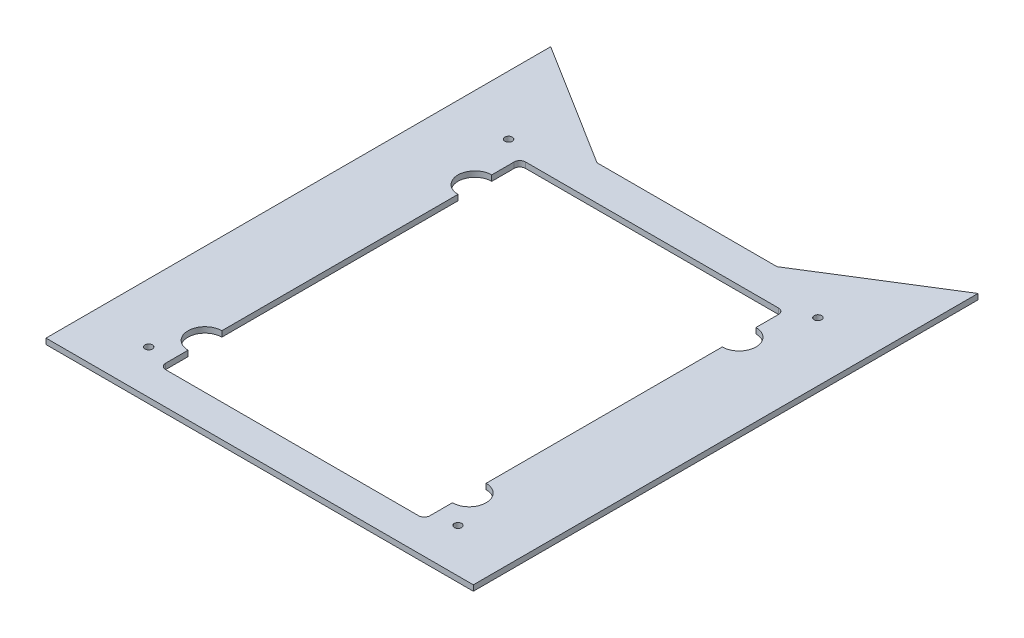
SolidWorks part; units mm, degrees
ref_plane "Front Plane" through (0, 0, 0) normal (0, 0, 1) x (1, 0, 0)
ref_plane "Top Plane" through (0, 0, 0) normal (0, 1, 0) x (1, 0, 0)
ref_plane "Right Plane" through (0, 0, 0) normal (1, 0, 0) x (0, 0, -1)
sketch "Sketch1" plane through (0, 0, 0) normal (0, 1, 0) x (1, 0, 0)
  line L17 (265.3132, -148.5502) -> (201.8132, -148.5502) construction
  line L18 (265.3132, -148.5502) -> (265.3132, -339.0502) construction
  line L19 (265.3132, -339.0502) -> (201.8132, -339.0502) construction
  line L20 (201.8132, -148.5502) -> (201.8132, -339.0502) construction
  line L21 (-153.7868, -148.5502) -> (-153.7868, -339.0502) construction
  line L22 (-217.2868, -339.0502) -> (-153.7868, -339.0502) construction
  line L23 (-217.2868, -148.5502) -> (-217.2868, -339.0502) construction
  line L24 (-217.2868, -148.5502) -> (-153.7868, -148.5502) construction
  line L25 (-242.6868, -133.4325) -> (-242.6868, -385.4912) construction
  line L26 (-191.8868, -438.1717) -> (-242.6868, -387.3717) construction
  line L27 (-191.8868, -438.1717) -> (239.9132, -438.1717) construction
  line L28 (239.9132, -438.1717) -> (290.7132, -387.3717) construction
  line L29 (290.7132, -387.3717) -> (290.7132, -133.3717) construction
  line L30 (290.7132, -133.3717) -> (176.4132, -82.5717) construction
  line L31 (176.4132, -82.5717) -> (176.4132, -133.3717) construction
  line L32 (176.4132, -133.3717) -> (74.8132, -196.8717) construction
  line L33 (74.8132, -196.8717) -> (-26.7868, -196.8717) construction
  line L34 (-128.3868, -133.3717) -> (-26.7868, -196.8717) construction
  line L35 (-128.3868, -82.5717) -> (-128.3868, -133.3717) construction
  line L36 (-242.6868, -133.3717) -> (-128.3868, -82.5717) construction
  line L37 (265.3132, -148.5502) -> (201.8132, -148.5502)
  line L38 (265.3132, -148.5502) -> (265.3132, -339.0502)
  line L39 (265.3132, -339.0502) -> (201.8132, -339.0502)
  line L40 (201.8132, -148.5502) -> (201.8132, -339.0502)
  line L41 (-153.7868, -148.5502) -> (-153.7868, -339.0502)
  line L42 (-217.2868, -339.0502) -> (-153.7868, -339.0502)
  line L43 (-217.2868, -148.5502) -> (-217.2868, -339.0502)
  line L44 (-217.2868, -148.5502) -> (-153.7868, -148.5502)
  line L45 (-242.6868, -133.4325) -> (-242.6868, -385.4912)
  line L46 (-191.8868, -438.1717) -> (-242.6868, -387.3717)
  line L47 (-191.8868, -438.1717) -> (239.9132, -438.1717)
  line L48 (239.9132, -438.1717) -> (290.7132, -387.3717)
  line L49 (290.7132, -387.3717) -> (290.7132, -133.3717)
  line L50 (290.7132, -133.3717) -> (176.4132, -82.5717)
  line L51 (176.4132, -82.5717) -> (176.4132, -133.3717)
  line L52 (176.4132, -133.3717) -> (74.8132, -196.8717)
  line L53 (74.8132, -196.8717) -> (-26.7868, -196.8717)
  line L54 (-128.3868, -133.3717) -> (-26.7868, -196.8717)
  line L55 (-128.3868, -82.5717) -> (-128.3868, -133.3717)
  line L56 (-242.6868, -133.3717) -> (-128.3868, -82.5717)
  line L57 (-242.6868, -133.4325) -> (-242.6868, -133.3717)
  line L58 (-242.6868, -385.4912) -> (-242.6868, -387.3717)
extrude "Boss-Extrude1" add sketch "Sketch1" along normal blind 3.175
sketch "Sketch3" plane through (0, 0, 0) normal (0, 1, 0) x (1, 0, 0)
  line L1 (-143.449, -203.465) -> (-143.449, -284.1354) construction
  line L2 (-143.449, -243.8002) -> (24.0132, -243.8002) construction
  line L3 (-191.8868, -438.1717) -> (239.9132, -438.1717) construction
  line L4 (-217.2868, -339.0502) -> (-153.7868, -339.0502) construction
  point P7 (24.0132, -438.1717)
  line B0 (24.0132, -13.4981) -> (24.0132, 49986.5019) construction
  circle B1 centre (-114.2782, -270.1255) radius 2.0828
  circle B2 centre (-143.449, -284.1354) radius 2.0828
  circle B3 centre (-114.2782, -217.4749) radius 2.0828
  circle B4 centre (-143.449, -203.465) radius 2.0828
  circle B5 centre (191.4754, -284.1354) radius 2.0828
  circle B6 centre (162.3046, -270.1255) radius 2.0828
  circle B7 centre (162.3046, -217.4749) radius 2.0828
  circle B8 centre (191.4754, -203.465) radius 2.0828
  dimension "D1" = 95.25
sketch_block_instance "motor_mount_pattern-1"
sketch_block "motor_mount_pattern"
extrude "Cut-Extrude2" cut sketch "Sketch3" along normal through all
sketch "Sketch4" plane through (0, 0, 0) normal (0, 1, 0) x (1, 0, 0)
  line L0 (24.0132, -54.7802) -> (24.0132, -50054.7802) construction
  line L1 (24.0132, -200460.6227) -> (24.0132, 249539.3773) construction
  circle A0 centre (111.3257, -210.2986) radius 2.0828
  circle A1 centre (111.3257, -413.4986) radius 2.0828
  circle A2 centre (-63.2993, -413.4986) radius 2.0828
  circle A3 centre (-63.2993, -210.2986) radius 2.0828
  line B0 (-50.5993, -216.6486) -> (98.6257, -216.6486)
  line B1 (-50.5993, -216.6486) -> (-50.5993, -232.5236)
  line B2 (-50.5993, -419.8486) -> (98.6257, -419.8486)
  line B3 (98.6257, -216.6486) -> (98.6257, -232.5236)
  line B4 (-50.5993, -251.5736) -> (-50.5993, -384.9236)
  line B5 (98.6257, -251.5736) -> (98.6257, -384.9236)
  line B6 (-50.5993, -403.9736) -> (-50.5993, -419.8486)
  line B7 (98.6257, -403.9736) -> (98.6257, -419.8486)
  arc B8 (-50.5993, -232.5236) -> (-50.5993, -251.5736) centre (-50.5993, -242.0486) ccw
  arc B9 (98.6257, -251.5736) -> (98.6257, -232.5236) centre (98.6257, -242.0486) ccw
  arc B10 (-50.5993, -384.9236) -> (-50.5993, -403.9736) centre (-50.5993, -394.4486) ccw
  arc B11 (98.6257, -403.9736) -> (98.6257, -384.9236) centre (98.6257, -394.4486) ccw
  dimension "D5" = 4.1656
  dimension "D1" = 12.7
  dimension "D2" = 6.35
  dimension "D3" = 12.7
  dimension "D4" = 6.35
sketch_block_instance "electronics_cutout-1"
sketch_block "electronics_cutout" parameters "D4"=17.1095, "D6"=25.5924, "D1"=203.2, "D2"=149.225, "D3"=35.6511, "D5"=24.7946
extrude "Cut-Extrude4" cut sketch "Sketch4" along normal through all
fillet "Fillet2" radius 3.175 4 edges at (-50.5993, 1.5875, 419.8486) (98.6257, 1.5875, 419.8486) (98.6257, 1.5875, 216.6486) (-50.5993, 1.5875, 216.6486)
sketch "Sketch6" plane through (0, 3.175, 0) normal (0, 1, 0) x (1, 0, 0)
  line L0 (-191.8868, -438.1717) -> (239.9132, -438.1717) construction
  line L1 (-96.6368, -438.1717) -> (-191.8868, -438.1717)
  line L2 (-191.8868, -438.1717) -> (-242.6868, -387.3717)
  line L3 (-242.6868, -387.3717) -> (-242.6868, -133.3717)
  line L4 (-242.6868, -133.3717) -> (-128.3868, -82.5717)
  line L5 (-128.3868, -82.5717) -> (-128.3868, -133.3717)
  line L6 (-128.3868, -133.3717) -> (-96.6368, -153.2154)
  line L7 (-26.7868, -196.8717) -> (-128.3868, -133.3717) construction
  line L8 (-96.6368, -153.2154) -> (-96.6368, -438.1717)
  line L10 (24.0132, -196.8717) -> (24.0132, -438.1717) construction
  line L11 (74.8132, -196.8717) -> (-26.7868, -196.8717) construction
  line L12 (176.4132, -133.3717) -> (144.6632, -153.2154)
  line L13 (176.4132, -82.5717) -> (176.4132, -133.3717)
  line L14 (290.7132, -133.3717) -> (176.4132, -82.5717)
  line L15 (290.7132, -387.3717) -> (290.7132, -133.3717)
  line L16 (239.9132, -438.1717) -> (290.7132, -387.3717)
  line L17 (144.6632, -438.1717) -> (239.9132, -438.1717)
  line L18 (144.6632, -153.2154) -> (144.6632, -438.1717)
  point P16 (24.0132, -438.1717)
  dimension "D1" = 120.65
extrude "Cut-Extrude5" cut sketch "Sketch6" against normal through all
